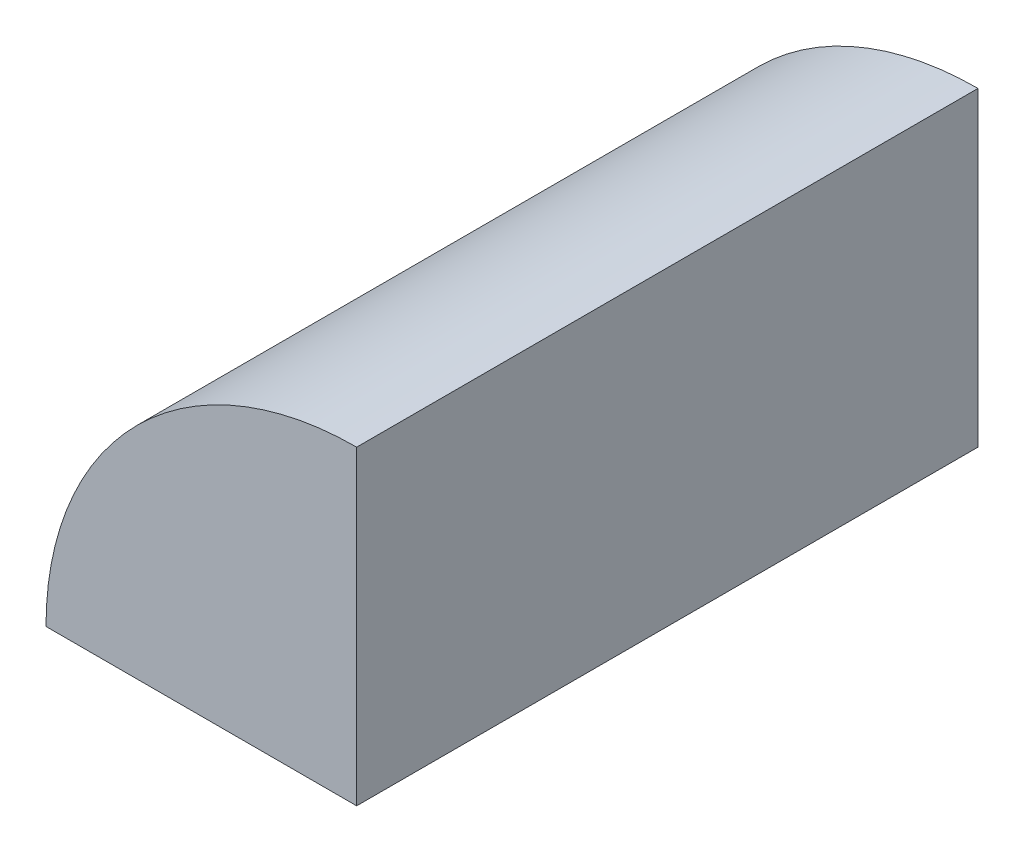
SolidWorks part; units mm, degrees
ref_plane "Alzado" through (0, 0, 0) normal (0, 0, 1) x (1, 0, 0)
ref_plane "Planta" through (0, 0, 0) normal (0, 1, 0) x (1, 0, 0)
ref_plane "Vista lateral" through (0, 0, 0) normal (1, 0, 0) x (0, 0, -1)
sketch "Croquis1" plane through (0, 0, 0) normal (0, 0, 1) x (1, 0, 0)
  line L0 (0, 25) -> (0, 0)
  line L1 (-25, 0) -> (0, 0)
  arc A0 (0, 25) -> (-25, 0) centre (0, 0) ccw
  dimension "D1" = 50
extrude "Saliente-Extruir1" add sketch "Croquis1" along normal blind 50
sketch "Croquis2" plane through (0, 0, 0) normal (0, 0, -1) x (-1, 0, 0)
  circle A0 centre (10.7882, 10.3887) radius 5
  dimension "D1" = 10
extrude "Cortar-Extruir1" cut sketch "Croquis2" against normal blind 10
